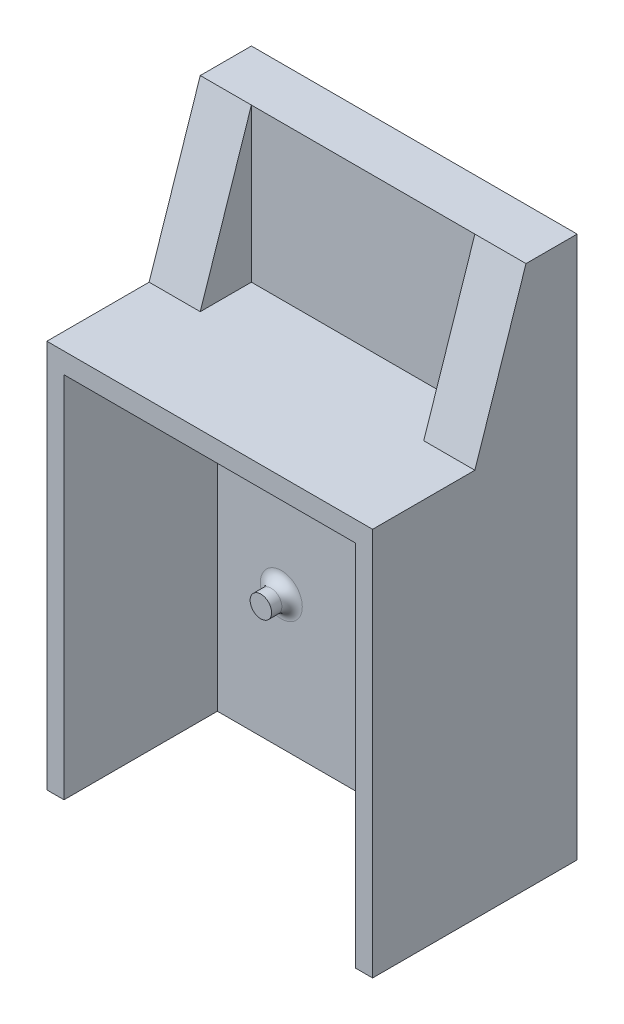
SolidWorks part; units mm, degrees
ref_plane "前视基准面" through (0, 0, 0) normal (0, 0, 1) x (1, 0, 0)
ref_plane "上视基准面" through (0, 0, 0) normal (0, 1, 0) x (1, 0, 0)
ref_plane "右视基准面" through (0, 0, 0) normal (1, 0, 0) x (0, 0, -1)
other "Configuration Table"
sketch "草图1" plane through (0, 0, 0) normal (0, 0, 1) x (1, 0, 0)
  line L0 (15.9265, 19) -> (0, 0)
  line L1 (-14.25, -17) -> (14.25, -17)
  line L2 (-14.25, -17) -> (-14.25, 17)
  line L3 (-14.25, 17) -> (14.25, 17)
  line L4 (14.25, -17) -> (14.25, 17)
  line L5 (0, 17) -> (0, -17) construction
  line L6 (-14.25, 0) -> (14.25, 0) construction
  line L7 (-15.9265, -19) -> (15.9265, -19)
  line L8 (-15.9265, -19) -> (-15.9265, 19)
  line L9 (-15.9265, 19) -> (15.9265, 19)
  line L10 (15.9265, -19) -> (15.9265, 19)
  line L11 (0, 19) -> (0, -19) construction
  line L12 (-15.9265, 0) -> (15.9265, 0) construction
  point P0 (0, 0)
  point P4 (0, 0)
  dimension "D1" = 28.5
  dimension "D2" = 34
  dimension "D3" = 2
extrude "凸台-拉伸1" add sketch "草图1" along normal blind 5
sketch "草图2" plane through (0, 0, 5) normal (0, 0, 1) x (1, 0, 0)
  line L0 (-14.25, -17) -> (-14.25, -19)
  line L2 (-14.25, -17) -> (-14.25, 17)
  line L3 (-14.25, 17) -> (14.25, 17)
  line L4 (-15.9265, -19) -> (15.9265, -19)
  line L5 (15.9265, -19) -> (15.9265, 19)
  line L6 (15.9265, 19) -> (-15.9265, 19)
  line L7 (-15.9265, 19) -> (-15.9265, -19)
  line L8 (-15.9265, -19) -> (15.9265, -19)
  line L9 (15.9265, -19) -> (15.9265, 19)
  line L10 (15.9265, 19) -> (-15.9265, 19)
  line L11 (-15.9265, 19) -> (-15.9265, -19)
  line L12 (14.25, -17) -> (14.25, 17)
  line L13 (0, 17) -> (0, -14.25) construction
  line L14 (-14.25, 0) -> (14.25, 0) construction
  line L15 (14.25, -17) -> (14.25, -19)
  line L16 (-14.25, -17) -> (14.25, -17)
  point P2 (0, 0)
  line M7 (-15.9265, -19) -> (15.9265, -19)
  line M8 (15.9265, -19) -> (15.9265, 19)
  line M9 (15.9265, 19) -> (-15.9265, 19)
  line M10 (-15.9265, 19) -> (-15.9265, -19)
  dimension "D2" = 28.5
  dimension "D3" = 34
  dimension "D1" = 0
extrude "凸台-拉伸2" add sketch "草图2" along normal blind 15 contours L12 L15 L8 L0 L2 L3 M8 M9 M10 M7
sketch "草图3" plane through (0, 0, 5) normal (0, 0, 1) x (1, 0, 0)
  line L0 (0, 0) -> (0, 12.3336) construction
  line L1 (0, 0) -> (-20.611, 0) construction
  line L2 (-14.25, 17) -> (-14.25, -19) construction
  line L3 (-14.25, 17) -> (14.25, 17) construction
  circle A0 centre (-8, 6) radius 1.05
  circle A1 centre (8, 6) radius 1.05
  circle A2 centre (-8, 6) radius 1.05
  circle A3 centre (8, 6) radius 1.05
  circle A4 centre (8, -6) radius 1.05
  circle A5 centre (-8, -6) radius 1.05
  circle A6 centre (8, -6) radius 1.05
  circle A7 centre (-8, -6) radius 1.05
  dimension "D2" = 11
  dimension "D3" = 2.1
  dimension "D1" = 6.25
extrude "凸台-拉伸3" add sketch "草图3" along normal blind 2 contours A0 | A1 | A5 | A4
sketch "草图4" plane through (0, 0, 0) normal (0, 0, -1) x (-1, 0, 0)
  line L0 (0, 0) -> (0, 14.3767) construction
  line L1 (15.9265, -19) -> (-15.9265, -19) construction
  line L2 (-15.9265, 19) -> (-30.9265, 19)
  line L3 (-15.9265, 19) -> (-15.9265, -19)
  line L4 (-15.9265, -19) -> (-30.9265, -19)
  line L5 (-30.9265, 19) -> (-30.9265, -19)
  line L6 (30.9265, 19) -> (30.9265, -19)
  line L7 (15.9265, -19) -> (30.9265, -19)
  line L8 (15.9265, 19) -> (15.9265, -19)
  line L9 (15.9265, 19) -> (30.9265, 19)
  line L11 (-15.9265, 19) -> (15.9265, 19)
  line L12 (-15.9265, 19) -> (-15.9265, 34)
  line L13 (-15.9265, 34) -> (15.9265, 34)
  line L14 (15.9265, 19) -> (15.9265, 34)
  line M12 (15.9265, 19) -> (-15.9265, 19)
  dimension "D1" = 15
  dimension "D2" = 15
extrude "凸台-拉伸4" add sketch "草图4" against normal blind 5 contours L14 L13 L12 M12
sketch "草图5" plane through (-15.9265, 0, 0) normal (-1, 0, 0) x (0, 0, 1)
  line L0 (5, 34) -> (10, 19)
  line L1 (10, 19) -> (5, 19)
  line L2 (5, 19) -> (5, 34)
  dimension "D1" = 5
extrude "凸台-拉伸5" add sketch "草图5" against normal blind 5
sketch "草图6" plane through (15.9265, 0, 0) normal (1, 0, 0) x (0, 0, -1)
  line L3 (-5, 19) -> (-5, 34)
  line L4 (-5, 34) -> (-10, 19)
  line L5 (-10, 19) -> (-5, 19)
  line L6 (-5, 19) -> (-5, 34)
  line L7 (-5, 34) -> (-10, 19)
  line L8 (-10, 19) -> (-5, 19)
  dimension "D1" = 0
extrude "凸台-拉伸6" add sketch "草图6" against normal blind 5
fillet "圆角1" radius 1 4 edges at (9.05, -6, 5) (9.05, 6, 5) (-6.95, 6, 5) (-6.95, -6, 5)
